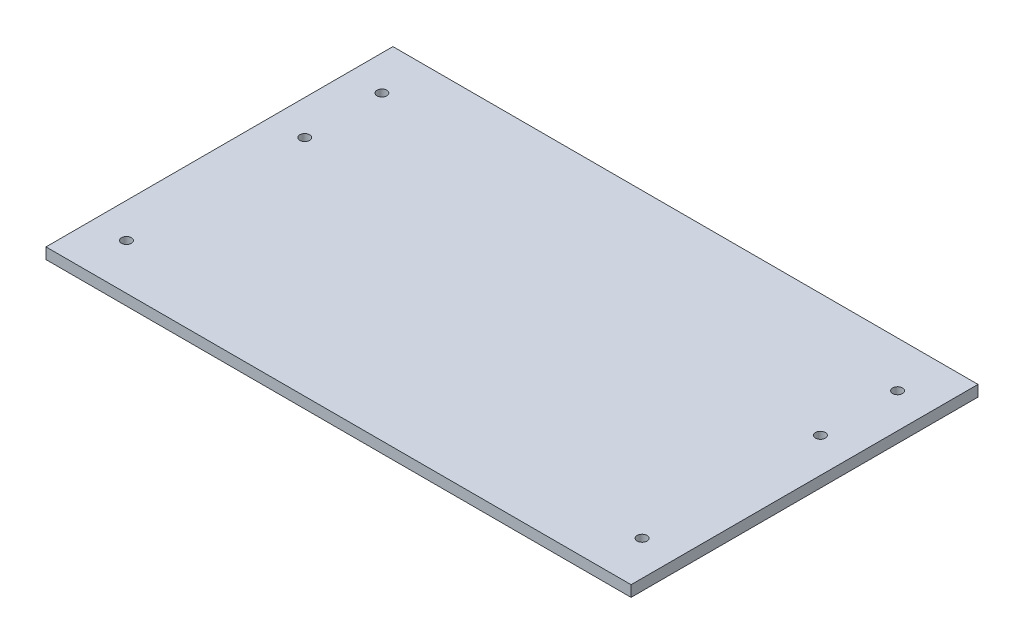
SolidWorks part; units mm, degrees
ref_plane "Front Plane" through (0, 0, 0) normal (0, 0, 1) x (1, 0, 0)
ref_plane "Top Plane" through (0, 0, 0) normal (0, 1, 0) x (1, 0, 0)
ref_plane "Right Plane" through (0, 0, 0) normal (1, 0, 0) x (0, 0, -1)
sketch "Sketch1" plane through (0, 0, 0) normal (0, 1, 0) x (1, 0, 0)
  line L1 (-84.325, -50) -> (84.325, -50)
  line L2 (-84.325, -50) -> (-84.325, 50)
  line L3 (-84.325, 50) -> (84.325, 50)
  line L4 (84.325, -50) -> (84.325, 50)
  line L5 (-84.325, -50) -> (84.325, 50) construction
  line L6 (-84.325, 50) -> (84.325, -50) construction
  point P0 (0, 0)
  dimension "D1" = 168.65
  dimension "D2" = 100
extrude "Boss-Extrude1" add sketch "Sketch1" along normal blind 3.18
sketch "Sketch2" plane through (0, 0, 0) normal (0, -1, 0) x (1, 0, 0)
  circle A1 centre (-74.325, 36.82) radius 1.4224
  circle A2 centre (-74.325, 36.82) radius 1.4224
  circle A3 centre (74.325, 36.82) radius 1.4224
  circle A4 centre (74.325, 36.82) radius 1.4224
  dimension "D1" = 0
  dimension "D2" = 0
extrude "Cut-Extrude1" cut sketch "Sketch2" against normal blind 3.18
mirror "Mirror1" about plane through (0, 0, 0) normal (0, 0, 1) of "Cut-Extrude1"
sketch "Sketch3" plane through (0, 3.18, 0) normal (0, 1, 0) x (1, 0, 0)
  circle A0 centre (74.325, 14.58) radius 1.4224 construction
  circle A1 centre (-74.325, 14.58) radius 1.4224
  circle A2 centre (-74.325, 14.58) radius 1.4224
  circle A3 centre (74.325, 14.58) radius 1.4224
  dimension "D1" = 0
extrude "Cut-Extrude2" cut sketch "Sketch3" against normal blind 3.18
